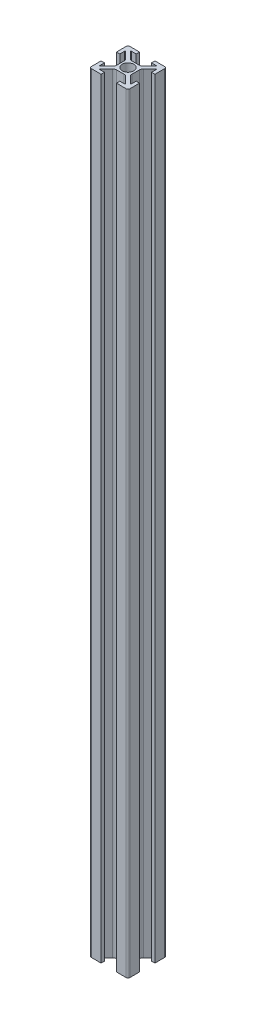
SolidWorks part; units mm, degrees
material "6063-T5"
ref_plane "Plano frontal" through (0, 0, 0) normal (0, 0, 1) x (1, 0, 0)
ref_plane "Plano superior" through (0, 0, 0) normal (0, 1, 0) x (1, 0, 0)
ref_plane "Plano direito" through (0, 0, 0) normal (1, 0, 0) x (0, 0, -1)
sketch "Esboço1" plane through (0, 0, 0) normal (0, 1, 0) x (1, 0, 0)
  line L1 (-10, 10) -> (10, 10)
  line L2 (-10, 10) -> (-10, -10)
  line L3 (-10, -10) -> (10, -10)
  line L4 (10, 10) -> (10, -10)
  line L5 (-10, 10) -> (10, -10) construction
  line L6 (-10, -10) -> (10, 10) construction
  circle A0 centre (0, 0) radius 3
  dimension "D1" = 6
  dimension "D2" = 20
  dimension "D3" = 20
extrude "Ressalto-extrusão1" add sketch "Esboço1" along normal mid plane 400
sketch "Esboço2" plane through (0, 200, 0) normal (0, 1, 0) x (1, 0, 0)
  line L0 (10, 10) -> (-10, 10) construction
  line L1 (-4, 4) -> (4, 4)
  line L2 (-4, 4) -> (-4, -4)
  line L3 (-4, -4) -> (4, -4)
  line L4 (4, 4) -> (4, -4)
  line L5 (-4, 4) -> (4, -4) construction
  line L6 (-4, -4) -> (4, 4) construction
  line L7 (0, 10) -> (0, -10) construction
  line L8 (-10, -10) -> (10, -10) construction
  line L9 (-4, 10) -> (4, 10)
  line L10 (-4, 10) -> (-4, 8.25)
  line L11 (4, 10) -> (4, 8.25)
  line L12 (-4, 8.25) -> (4, 8.25)
  line L13 (-7.05, 8.25) -> (7.05, 8.25)
  line L14 (-7.05, 8.25) -> (-2.8, 4)
  line L15 (7.05, 8.25) -> (2.8, 4)
  line L16 (2.8, 4) -> (-2.8, 4)
  point P0 (0, 0)
  point P19 (0, 8.25)
  line M7 (10, 10) -> (-10, 10)
  dimension "D1" = 8
  dimension "D2" = 8
  dimension "D3" = 1.75
  dimension "D4" = 8
  dimension "D5" = 14.1
  dimension "D6" = 45
  dimension "D7" = 45
extrude "Corte-extrusão1" cut sketch "Esboço2" against normal through all contours L15 L13 L12 L14 L1 | L10 L12 L11 M7
pattern_circular "PadrãoCircular2" count 4 over 360 about axis through (0, 0, 0) along (0, 1, 0) of "Corte-extrusão1"
fillet "Filete2" radius 1 4 edges at (10, 0, 10) (-10, 0, 10) (-10, 0, -10) (10, 0, -10)
fillet "Filete3" radius 2 8 edges at (2.8, 0, 4) (-4, 0, 2.8) (2.8, 0, -4) (-2.8, 0, -4) (4, 0, 2.8) (4, 0, -2.8) (-4, 0, -2.8) (-2.8, 0, 4)
fillet "Filete4" radius 0.25 8 edges at (8.25, 0, 7.05) (7.05, 0, 8.25) (-8.25, 0, 7.05) (-7.05, 0, 8.25) (8.25, 0, -7.05) (7.05, 0, -8.25) (-8.25, 0, -7.05) (-7.05, 0, -8.25)
